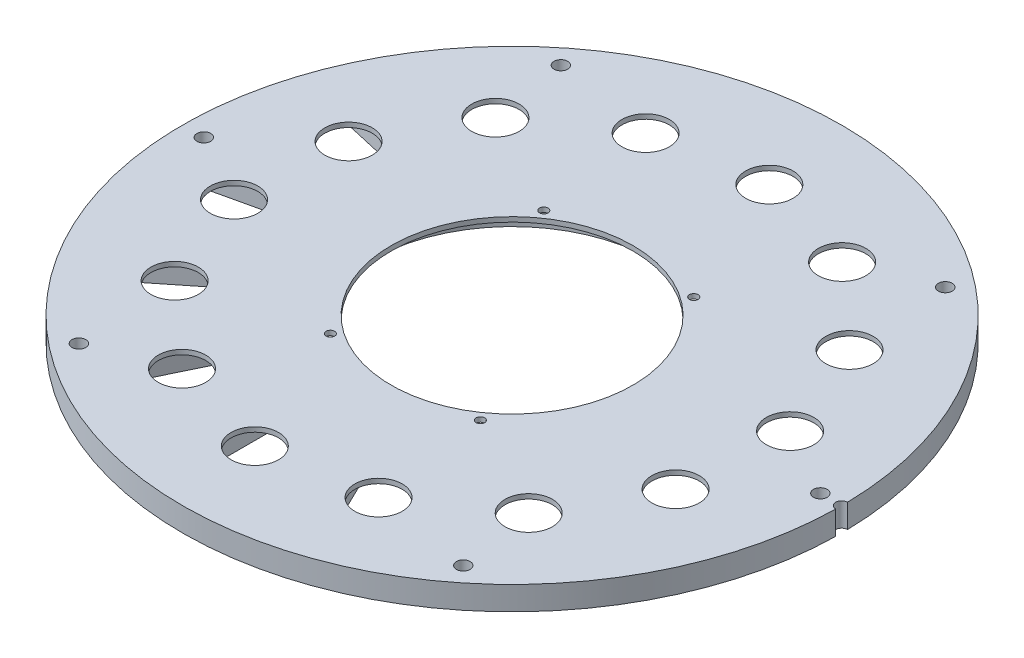
SolidWorks part; units mm, degrees
material "5052-O"
ref_plane "正面" through (0, 0, 0) normal (0, 0, 1) x (1, 0, 0)
ref_plane "平面" through (0, 0, 0) normal (0, 1, 0) x (1, 0, 0)
ref_plane "右側面" through (0, 0, 0) normal (1, 0, 0) x (0, 0, -1)
sketch "ｽｹｯﾁ1" plane through (0, 0, 0) normal (0, 1, 0) x (1, 0, 0)
  circle A0 centre (0, 0) radius 139
  dimension "D1" = 278
extrude "ﾎﾞｽ - 押し出し1" add sketch "ｽｹｯﾁ1" along normal blind 10
sketch "ｽｹｯﾁ2" plane through (0, 0, 0) normal (0, -1, 0) x (1, 0, 0)
  line L0 (0, 119) -> (0, 85) construction
  line L1 (18.5, 119) -> (18.5, 85)
  line L2 (-18.5, 119) -> (-18.5, 85)
  arc A0 (18.5, 119) -> (-18.5, 119) centre (0, 119) ccw
  arc A1 (-18.5, 85) -> (18.5, 85) centre (0, 85) ccw
  point P2 (0, 102)
  dimension "D2" = 37
  dimension "D1" = 34
  dimension "D3" = 102
extrude "電池用窪み" cut sketch "ｽｹｯﾁ2" against normal blind 8
pattern_circular "円形ﾊﾟﾀｰﾝ1" count 14 over 360 about axis through (0, 0, 0) along (0, 1, 0) of "電池用窪み"
sketch "ｽｹｯﾁ3" plane through (0, 0, 0) normal (0, -1, 0) x (-1, 0, 0)
  circle A0 centre (0, 0) radius 51
  dimension "D1" = 102
extrude "キール用穴" cut sketch "ｽｹｯﾁ3" against normal through all
sketch "ｽｹｯﾁ5" plane through (0, 8, 0) normal (0, -1, 0) x (1, 0, 0)
  circle A0 centre (-6.5, 102) radius 10
  dimension "D1" = 20
  dimension "D2" = 102
  dimension "D3" = 6.5
extrude "電池配線取り出し穴" cut sketch "ｽｹｯﾁ5" against normal through all
pattern_circular "円形ﾊﾟﾀｰﾝ2" count 14 over 360 about axis through (0, 0, 0) along (0, 1, 0) of "電池配線取り出し穴"
sketch "ｽｹｯﾁ6" plane through (0, 0, 0) normal (0, -1, 0) x (1, 0, 0)
  line L0 (0, 0) -> (130, 0) construction
  circle A0 centre (130, 0) radius 5
  dimension "D1" = 10
  dimension "D2" = 130
sketch "ｽｹｯﾁ9" plane through (0, 10, 0) normal (0, 1, 0) x (1, 0, 0)
  circle A0 centre (-31.6228, 45) radius 1.5
  circle A1 centre (-31.6228, 45) radius 3
  dimension "D1" = 3
  dimension "D4" = 6
  dimension "D2" = 55
  dimension "D3" = 45
hole_wizard "M3(六角スペーサ) キールへの固定穴" positions "3Dｽｹｯﾁ2" profile "ｽｹｯﾁ10" hole size "M3" standard "ISO" end condition through all
sketch3d "3Dｽｹｯﾁ2"
  point P0 (-31.6228, 10, -45)
sketch "ｽｹｯﾁ10" plane through (-31.6228, 10, -45) normal (1, 0, 0) x (0, 0, 1)
  line L0 (0, 0) -> (0, 10)
  line L1 (0, 10) -> (1.8, 10)
  line L2 (1.8, 10) -> (1.8, 0)
  line L5 (1.8, 0) -> (0, 0)
  line L11 (0, -6.35) -> (0, 107.95) construction
  dimension "通し穴の直径" = 3.6
  dimension "通し穴の深さ" = 10
mirror "ﾐﾗｰ1" about plane through (0, 0, 0) normal (0, 0, 1) of "M3(六角スペーサ) キールへの固定穴"
mirror "ﾐﾗｰ2" about plane through (0, 0, 0) normal (1, 0, 0) of "ﾐﾗｰ1", "M3(六角スペーサ) キールへの固定穴"
hole_wizard "M5supportingpole用" positions "3Dｽｹｯﾁ3" profile "ｽｹｯﾁ12" hole size "M5" standard "ISO" end condition through all
sketch3d "3Dｽｹｯﾁ3"
  point P0 (130, 0, 0)
sketch "ｽｹｯﾁ12" plane through (130, 0, 0) normal (1, 0, 0) x (0, 0, -1)
  line L0 (0, 0) -> (0, 10)
  line L1 (0, 10) -> (2.9, 10)
  line L2 (2.9, 10) -> (2.9, 0)
  line L5 (2.9, 0) -> (0, 0)
  line L11 (0, -6.35) -> (0, 107.95) construction
  dimension "通し穴の直径" = 5.8
  dimension "通し穴の深さ" = 10
sketch "ｽｹｯﾁ13" plane through (0, 0, 0) normal (0, -1, 0) x (1, 0, 0)
  circle A0 centre (81.0537, 101.6381) radius 3
  point P2 (130, 0)
  dimension "D1" = 6
  dimension "D2" = 130
  dimension "D3" = 51.429
hole_wizard "M5 supporting_pole用" positions "3Dｽｹｯﾁ4" profile "ｽｹｯﾁ14" hole size "M5" standard "JIS" end condition through all
sketch3d "3Dｽｹｯﾁ4"
  point P0 (81.0537, 0, 101.6381)
sketch "ｽｹｯﾁ14" plane through (81.0537, 0, 101.6381) normal (1, 0, 0) x (0, 0, -1)
  line L0 (0, 0) -> (0, 10)
  line L1 (0, 10) -> (2.9, 10)
  line L2 (2.9, 10) -> (2.9, 0)
  line L5 (2.9, 0) -> (0, 0)
  line L11 (0, -6.35) -> (0, 107.95) construction
  dimension "通し穴の直径" = 5.8
  dimension "通し穴の深さ" = 10
mirror "ﾐﾗｰ3" about plane through (0, 0, 0) normal (0, 0, 1) of "M5 supporting_pole用", "M5supportingpole用"
mirror "ﾐﾗｰ4" about plane through (0, 0, 0) normal (1, 0, 0) of "ﾐﾗｰ3", "M5 supporting_pole用"
sketch "ｽｹｯﾁ15" plane through (0, 0, 0) normal (0, -1, 0) x (1, 0, 0)
  circle A0 centre (81.0537, 101.6381) radius 5.1
  circle A1 centre (130, 0) radius 5.1
  dimension "D1" = 10.2
  dimension "D2" = 10.2
extrude "ｶｯﾄ - 押し出し7" cut sketch "ｽｹｯﾁ15" against normal blind 5
mirror "ﾐﾗｰ5" about plane through (0, 0, 0) normal (0, 0, 1) of "ｶｯﾄ - 押し出し7"
mirror "ﾐﾗｰ6" about plane through (0, 0, 0) normal (1, 0, 0) of "ﾐﾗｰ5", "ｶｯﾄ - 押し出し7"
sketch "ｽｹｯﾁ16" plane through (0, 0, 0) normal (0, -1, 0) x (1, 0, 0)
  circle A0 centre (0, 0) radius 60
  circle A1 centre (0, 0) radius 51 construction
  circle A2 centre (0, 0) radius 51
  dimension "D1" = 120
extrude "ｶｯﾄ - 押し出し8" cut sketch "ｽｹｯﾁ16" against normal blind 8
sketch "ｽｹｯﾁ18" plane through (0, 10, 0) normal (0, 1, 0) x (1, 0, 0)
  line L0 (0, 0) -> (139, 0) construction
  circle A0 centre (139, 0) radius 2.5
  circle A1 centre (0, 0) radius 139 construction
  dimension "D1" = 5
extrude "ｶｯﾄ - 押し出し10" cut sketch "ｽｹｯﾁ18" against normal through all
